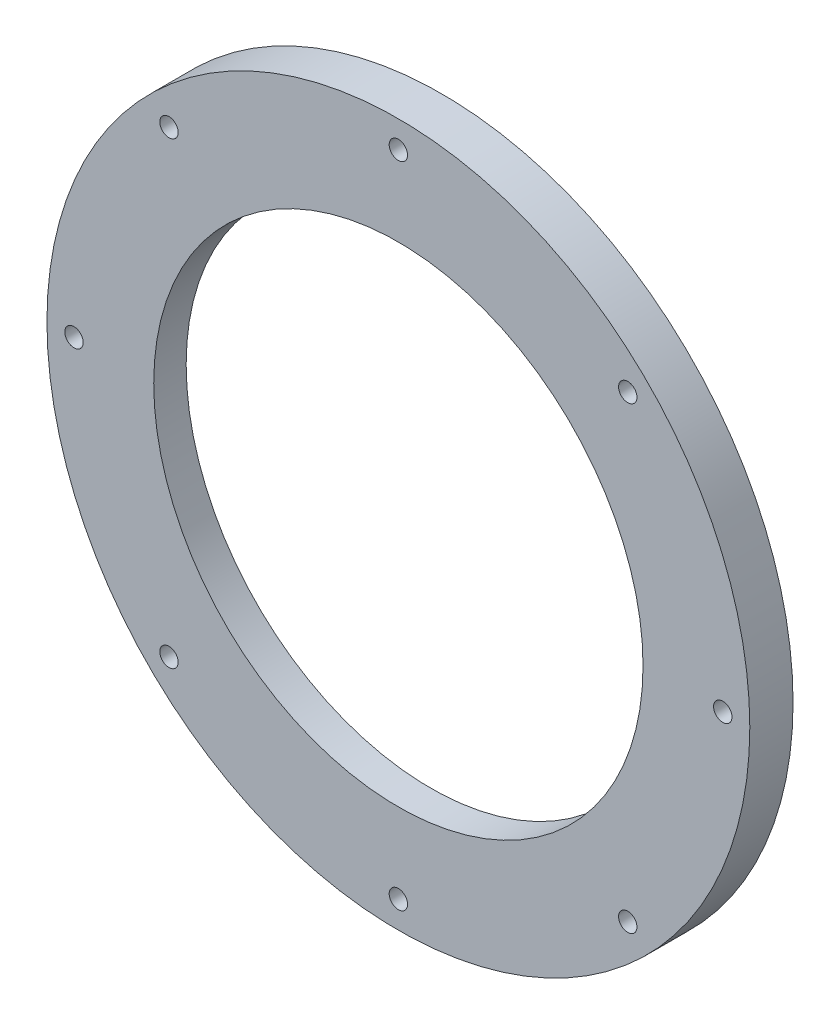
SolidWorks part; units mm, degrees
material "7075-O (SS)"
ref_plane "Front" through (0, 0, 0) normal (0, 0, 1) x (1, 0, 0)
ref_plane "Top" through (0, 0, 0) normal (0, 1, 0) x (1, 0, 0)
ref_plane "Right" through (0, 0, 0) normal (1, 0, 0) x (0, 0, -1)
sketch "Croquis1" plane through (0, 0, 0) normal (0, 0, 1) x (1, 0, 0)
  circle A0 centre (0, 0) radius 65
  circle A1 centre (0, 0) radius 45.25
  dimension "DiametroExterior" = 130
  dimension "D2" = 90.5
extrude "Saliente-Extruir1" add sketch "Croquis1" along normal mid plane 8
hole_wizard "Taladro de margen para M31" positions "Croquis2" profile "Croquis3" hole size "M3" standard "Ansi Metric" end condition up to next
sketch "Croquis2" plane through (0, 0, 4) normal (0, 0, 1) x (1, 0, 0)
  line L0 (0, -4.4) -> (0, 4.4) construction
  point P0 (0, 60)
  point P10 (42.4264, 42.4264)
  point P11 (60, 0)
  point P12 (42.4264, -42.4264)
  point P13 (0, -60)
  point P14 (-42.4264, -42.4264)
  point P15 (-60, 0)
  point P16 (-42.4264, 42.4264)
  dimension "D1" = 60
  dimension "D2" = 8
sketch "Croquis3" plane through (0, 60, 4) normal (1, 0, 0) x (0, -1, 0)
  line L0 (0, 0) -> (0, 8)
  line L1 (0, 8) -> (1.7, 8)
  line L2 (1.7, 8) -> (1.7, 0)
  line L5 (1.7, 0) -> (0, 0)
  line L11 (0, -6.35) -> (0, 107.95) construction
  dimension "Diámetro de taladro hasta el siguiente" = 3.4
  dimension "Profundidad de taladro hasta el siguiente" = 8
sketch "Croquis4" plane through (0, 0, -4) normal (0, 0, -1) x (-1, 0, 0)
  circle A0 centre (0, 0) radius 50
  dimension "D1" = 100
extrude "Cortar-Extruir1" cut sketch "Croquis4" against normal blind 2
